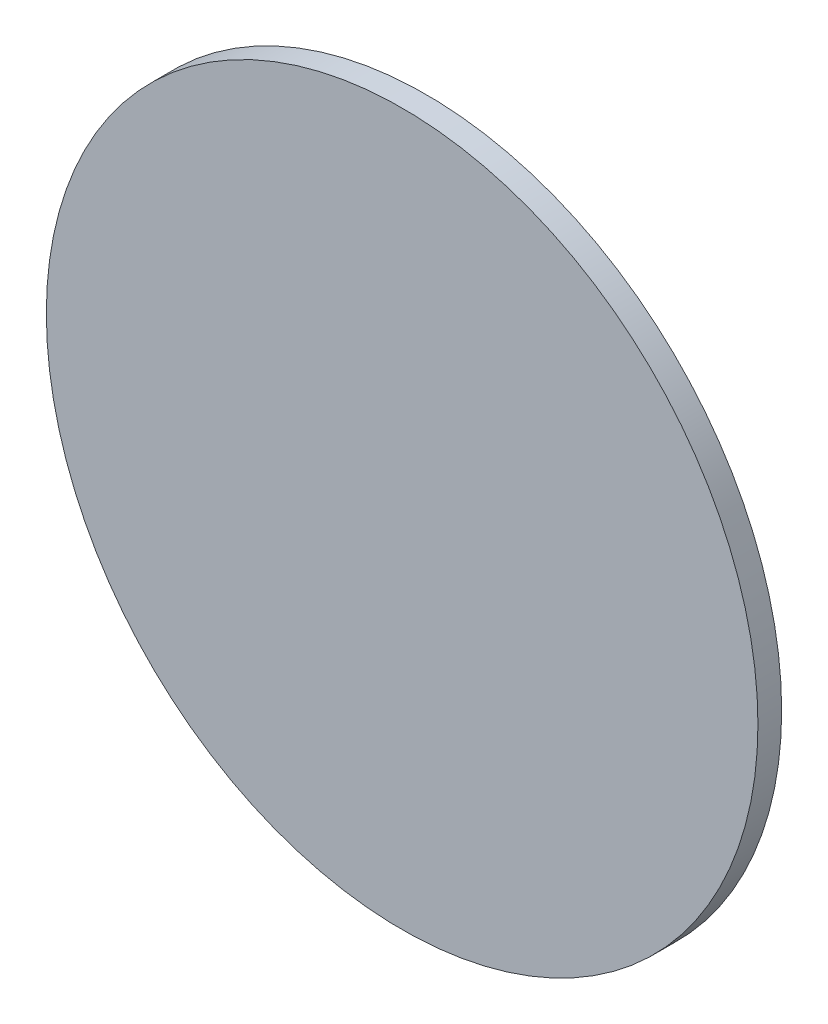
SolidWorks part; units mm, degrees
ref_plane "Front Plane" through (0, 0, 0) normal (0, 0, 1) x (1, 0, 0)
ref_plane "Top Plane" through (0, 0, 0) normal (0, 1, 0) x (1, 0, 0)
ref_plane "Right Plane" through (0, 0, 0) normal (1, 0, 0) x (0, 0, -1)
sketch "Sketch1" plane through (0, 0, 0) normal (0, 0, 1) x (1, 0, 0)
  circle A0 centre (0, 0) radius 150
  dimension "D1" = 300
extrude "Boss-Extrude1" add sketch "Sketch1" along normal blind 10
